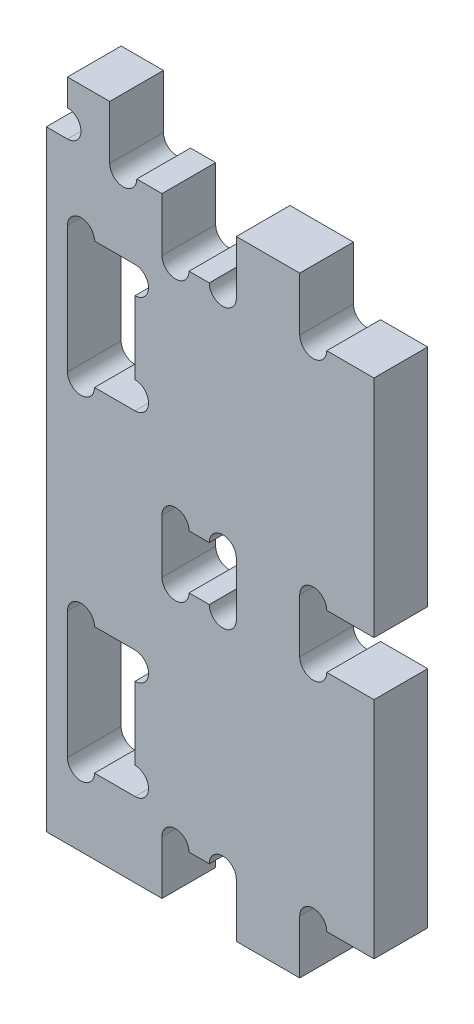
SolidWorks part; units mm, degrees
ref_plane "Front Plane" through (0, 0, 0) normal (0, 0, 1) x (1, 0, 0)
ref_plane "Top Plane" through (0, 0, 0) normal (0, 1, 0) x (1, 0, 0)
ref_plane "Right Plane" through (0, 0, 0) normal (1, 0, 0) x (0, 0, -1)
sketch "Sketch1" plane through (0, 0, 0) normal (0, 0, 1) x (1, 0, 0)
  line L0 (54.94, 144.4) -> (54.94, 131.7)
  line L1 (0, 0) -> (72.51, 0) construction
  line L2 (0, 0) -> (0, 144.4) construction
  line L3 (0, 144.4) -> (72.51, 144.4) construction
  line L4 (72.51, 0) -> (72.51, 144.4) construction
  line L5 (54.94, 131.7) -> (72.51, 131.7)
  line L6 (54.94, 144.4) -> (39.94, 144.4)
  line L7 (39.94, 144.4) -> (39.94, 131.7)
  line L8 (39.94, 131.7) -> (22.36, 131.7)
  line L9 (22.36, 131.7) -> (22.36, 144.4)
  line L10 (-5, 144.4) -> (0, 144.4)
  line L11 (0, 144.4) -> (0, 157.1)
  line L12 (-5, 144.4) -> (-5, 0)
  line L13 (-5, 0) -> (0, 0) construction
  line L14 (72.51, 131.7) -> (72.51, 78.5)
  line L15 (72.51, 78.5) -> (54.94, 78.5)
  line L16 (54.94, 78.5) -> (54.94, 65.8)
  line L17 (54.94, 65.8) -> (72.51, 65.8)
  line L18 (72.51, 65.8) -> (72.51, 12.7)
  line L19 (72.51, 12.7) -> (54.94, 12.7)
  line L20 (54.94, 12.7) -> (54.94, 0)
  line L21 (54.94, 0) -> (39.94, 0)
  line L22 (54.94, 78.5) -> (39.94, 78.5) construction
  line L23 (39.94, 78.5) -> (39.94, 131.7) construction
  line L24 (54.94, 12.7) -> (39.94, 12.7) construction
  line L25 (39.94, 12.7) -> (39.94, 78.5) construction
  line L26 (22.36, 0) -> (-5, 0)
  line L27 (39.94, 78.5) -> (22.36, 78.5)
  line L28 (39.94, 78.5) -> (39.94, 65.8)
  line L29 (39.94, 65.8) -> (22.36, 65.8)
  line L30 (22.36, 78.5) -> (22.36, 65.8)
  line L31 (39.94, 12.7) -> (22.36, 12.7)
  line L32 (39.94, 12.7) -> (39.94, 0)
  line L34 (22.36, 12.7) -> (22.36, 0)
  line L37 (0, 157.1) -> (10, 157.1)
  line L38 (0, 126.7) -> (15.98, 126.7)
  line L39 (0, 126.7) -> (0, 96.7)
  line L40 (0, 96.7) -> (15.98, 96.7)
  line L41 (15.98, 126.7) -> (15.98, 96.7)
  line L42 (0, 17.7) -> (15.98, 17.7)
  line L43 (0, 17.7) -> (0, 47.7)
  line L44 (0, 47.7) -> (15.98, 47.7)
  line L45 (15.98, 17.7) -> (15.98, 47.7)
  line L46 (10, 157.1) -> (10, 144.4)
  line L47 (10, 144.4) -> (22.36, 144.4)
  dimension "D1" = 144.4
  dimension "D2" = 56.53
  dimension "D3" = 5
  dimension "D4" = 15
  dimension "D5" = 17.57
  dimension "D6" = 50.15
  dimension "D7" = 12.7
  dimension "D8" = 65.9
  dimension "D9" = 131.7
  dimension "D11" = 5
  dimension "D12" = 5
  dimension "D13" = 30
  dimension "D14" = 15.98
  dimension "D15" = 12.7
  dimension "D16" = 10
extrude "Boss-Extrude1" add sketch "Sketch1" along normal blind 12.7
sketch "Sketch2" plane through (0, 0, 12.7) normal (0, 0, 1) x (1, 0, 0)
  line L0 (72.51, 131.7) -> (54.94, 131.7) construction
  line L1 (54.94, 78.5) -> (72.51, 78.5) construction
  line L2 (72.51, 65.8) -> (54.94, 65.8) construction
  line L3 (39.94, 78.5) -> (22.36, 78.5) construction
  line L4 (22.36, 65.8) -> (39.94, 65.8) construction
  line L5 (39.94, 12.7) -> (22.36, 12.7) construction
  line L7 (54.94, 12.7) -> (72.51, 12.7) construction
  line L9 (39.94, 131.7) -> (22.36, 131.7) construction
  line L10 (22.36, 144.4) -> (10, 144.4) construction
  line L11 (15.98, 96.7) -> (15.98, 126.7) construction
  line L12 (15.98, 126.7) -> (0, 126.7) construction
  line L13 (0, 96.7) -> (15.98, 96.7) construction
  line L14 (15.98, 17.7) -> (15.98, 47.7) construction
  line L15 (0, 17.7) -> (15.98, 17.7) construction
  line L16 (15.98, 47.7) -> (0, 47.7) construction
  line L17 (0, 157.1) -> (0, 144.4) construction
  circle A0 centre (58.14, 131.7) radius 3.2
  circle A1 centre (58.14, 78.5) radius 3.2
  circle A2 centre (58.14, 65.8) radius 3.2
  circle A3 centre (36.74, 78.5) radius 3.2
  circle A4 centre (36.74, 65.8) radius 3.2
  circle A5 centre (25.56, 78.5) radius 3.2
  circle A6 centre (25.56, 65.8) radius 3.2
  circle A7 centre (25.56, 12.7) radius 3.2
  circle A10 centre (36.74, 12.7) radius 3.2
  circle A11 centre (58.14, 12.7) radius 3.2
  circle A13 centre (36.74, 131.7) radius 3.2
  circle A14 centre (25.56, 131.7) radius 3.2
  circle A15 centre (13.2, 144.4) radius 3.2
  circle A16 centre (15.98, 123.5) radius 3.2
  circle A17 centre (3.2, 126.7) radius 3.2
  circle A18 centre (3.2, 96.7) radius 3.2
  circle A19 centre (15.98, 99.9) radius 3.2
  circle A20 centre (15.98, 44.5) radius 3.2
  circle A21 centre (15.98, 20.9) radius 3.2
  circle A22 centre (3.2, 17.7) radius 3.2
  circle A23 centre (3.2, 47.7) radius 3.2
  circle A24 centre (0, 147.6) radius 3.2
  dimension "D1" = 6.4
extrude "Cut-Extrude1" cut sketch "Sketch2" against normal through all
